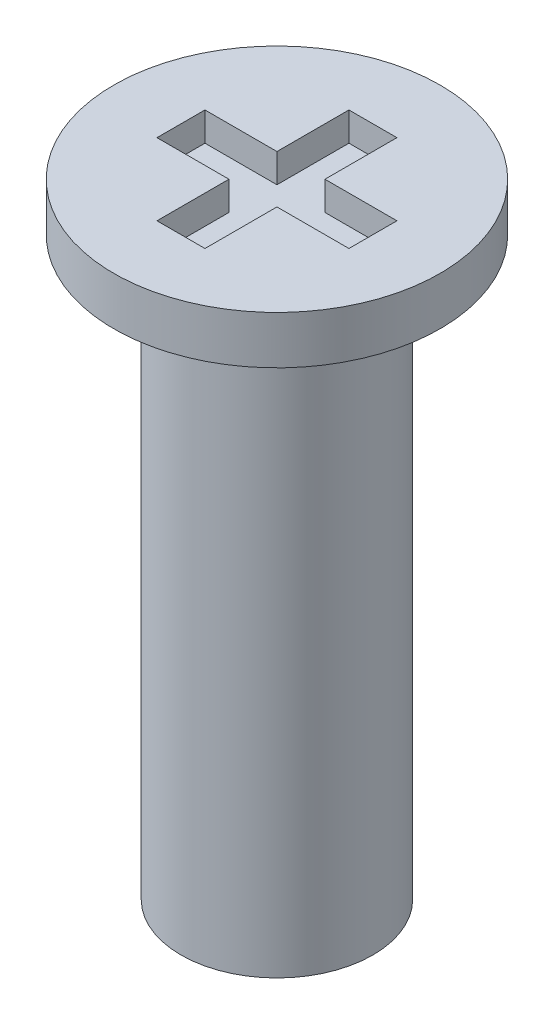
SolidWorks part; units mm, degrees
material "S45C"
ref_plane "正面" through (0, 0, 0) normal (0, 0, 1) x (1, 0, 0)
ref_plane "平面" through (0, 0, 0) normal (0, 1, 0) x (1, 0, 0)
ref_plane "右側面" through (0, 0, 0) normal (1, 0, 0) x (0, 0, -1)
sketch "ｽｹｯﾁ1" plane through (0, 0, 0) normal (0, 0, 1) x (1, 0, 0)
  line L0 (0, 0) -> (1.7, 0)
  line L1 (1.7, 0) -> (1.7, -0.5)
  line L2 (1.7, -0.5) -> (1, -0.5)
  line L3 (1, -0.5) -> (1, -6.5)
  line L4 (1, -6.5) -> (0, -6.5)
  line L5 (0, -6.5) -> (0, 0)
  dimension "D1" = 1.7
  dimension "D2" = 0.5
  dimension "D3" = 1
  dimension "D4" = 6
revolve "回転1" add sketch "ｽｹｯﾁ1" angle 360 about L5
sketch "ｽｹｯﾁ2" plane through (0, 0, 0) normal (0, 1, 0) x (1, 0, 0)
  line L1 (-0.25, 0) -> (0.25, 0)
  line L2 (-0.25, 0) -> (-0.25, 1)
  line L3 (-0.25, 1) -> (0.25, 1)
  line L4 (0.25, 0) -> (0.25, 1)
  line L5 (-0.25, 0) -> (0.25, 1) construction
  line L6 (-0.25, 1) -> (0.25, 0) construction
  point P4 (0, 0.5)
  dimension "D1" = 0
  dimension "D2" = 0.5
  dimension "D3" = 1
  dimension "D4" = 0
extrude "ｶｯﾄ - 押し出し1" cut sketch "ｽｹｯﾁ2" against normal blind 0.3
pattern_circular "円形ﾊﾟﾀｰﾝ1" count 4 over 360 about axis through (0, 0, 0) along (0, 1, 0) of "ｶｯﾄ - 押し出し1"
